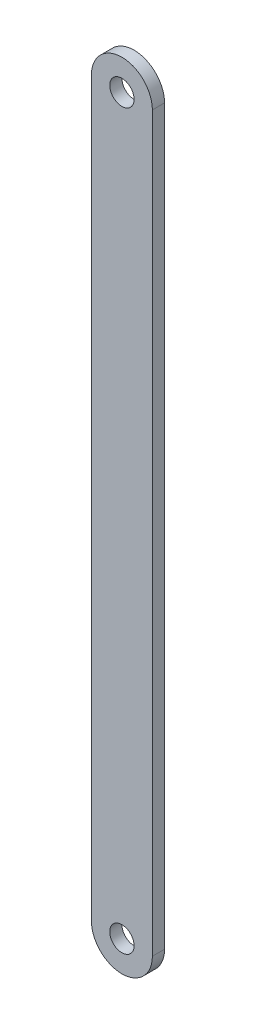
SolidWorks part; units mm, degrees
ref_plane "Alzado" through (0, 0, 0) normal (0, 0, 1) x (1, 0, 0)
ref_plane "Planta" through (0, 0, 0) normal (0, 1, 0) x (1, 0, 0)
ref_plane "Vista lateral" through (0, 0, 0) normal (1, 0, 0) x (0, 0, -1)
sketch "Croquis1" plane through (0, 0, 0) normal (0, 0, 1) x (1, 0, 0)
  line L0 (0, 0) -> (50, 0) construction
  line L1 (50, 0) -> (50, 601.7)
  line L2 (50, 601.7) -> (0, 601.7) construction
  line L3 (0, 601.7) -> (0, 0)
  arc A0 (0, 0) -> (50, 0) centre (25, 0) ccw
  arc A1 (50, 601.7) -> (0, 601.7) centre (25, 601.7) ccw
  circle A2 centre (25, 601.7) radius 10
  circle A3 centre (25, 0) radius 10
  dimension "D3" = 20
  dimension "D4" = 20
  dimension "D1" = 50
  dimension "D2" = 601.7
extrude "Saliente-Extruir1" add sketch "Croquis1" along normal blind 10
